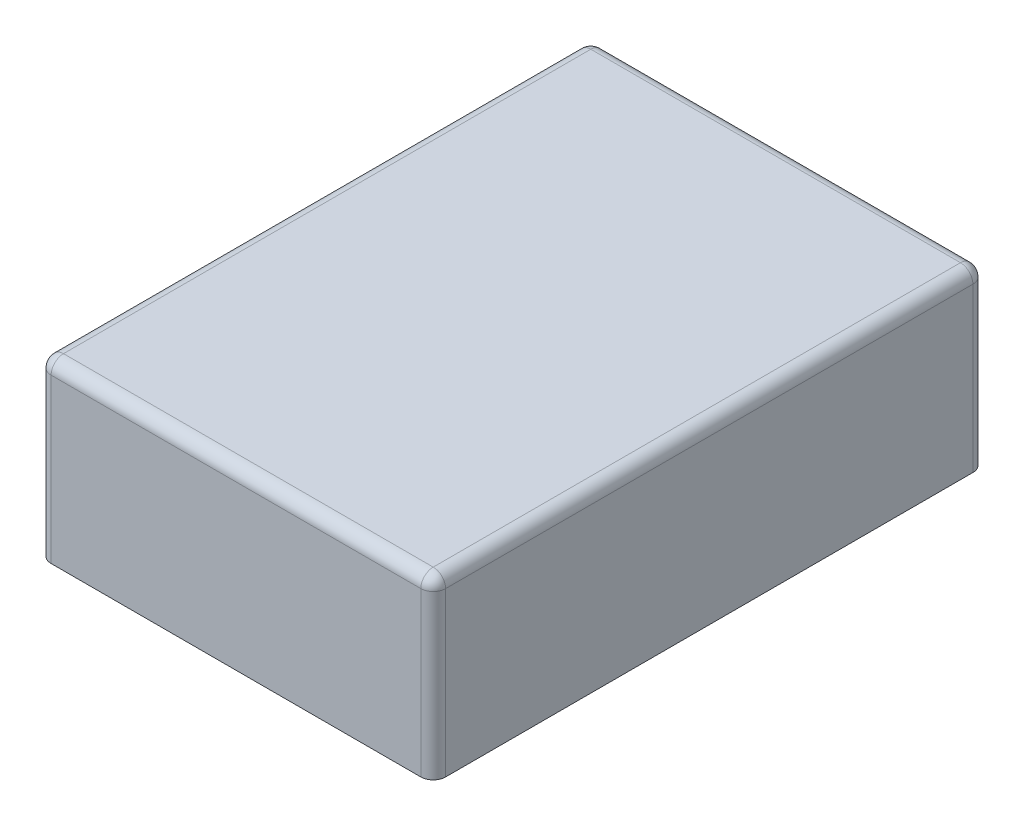
SolidWorks part; units mm, degrees
ref_plane "Front Plane" through (0, 0, 0) normal (0, 0, 1) x (1, 0, 0)
ref_plane "Top Plane" through (0, 0, 0) normal (0, 1, 0) x (1, 0, 0)
ref_plane "Right Plane" through (0, 0, 0) normal (1, 0, 0) x (0, 0, -1)
sketch "Sketch1" plane through (0, 0, 0) normal (0, 1, 0) x (1, 0, 0)
  line L1 (-45.2445, 63.4234) -> (44.1555, 63.4234)
  line L2 (-45.2445, 63.4234) -> (-45.2445, -64.0766)
  line L3 (-45.2445, -64.0766) -> (44.1555, -64.0766)
  line L4 (44.1555, 63.4234) -> (44.1555, -64.0766)
extrude "Extrude-Thin1" add sketch "Sketch1" along normal blind 37.45 thin thin type one direction wall 3
sketch "Sketch2" plane through (0, 37.45, 0) normal (0, 1, 0) x (1, 0, 0)
  line L1 (-48.2445, 66.4234) -> (47.1555, 66.4234)
  line L2 (-48.2445, 66.4234) -> (-48.2445, -67.0766)
  line L3 (-48.2445, -67.0766) -> (47.1555, -67.0766)
  line L4 (47.1555, 66.4234) -> (47.1555, -67.0766)
extrude "Boss-Extrude1" add sketch "Sketch2" along normal blind 5
fillet "Fillet3" radius 3 4 edges at (-48.2445, 21.225, 67.0766) (47.1555, 21.225, 67.0766) (47.1555, 21.225, -66.4234) (-48.2445, 21.225, -66.4234)
fillet "Fillet4" radius 3 8 edges at (46.2768, 42.45, -65.5447) (46.2768, 42.45, 66.198) (-47.3658, 42.45, 66.198) (-47.3658, 42.45, -65.5447) (47.1555, 42.45, 0.3266) (-0.5445, 42.45, 67.0766) (-48.2445, 42.45, 0.3266) (-0.5445, 42.45, -66.4234)
